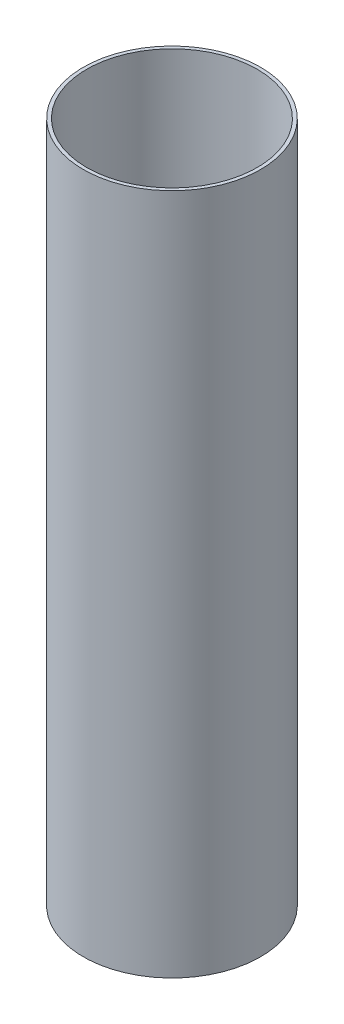
SolidWorks part; units mm, degrees
ref_plane "Front Plane" through (0, 0, 0) normal (0, 0, 1) x (1, 0, 0)
ref_plane "Top Plane" through (0, 0, 0) normal (0, 1, 0) x (1, 0, 0)
ref_plane "Right Plane" through (0, 0, 0) normal (1, 0, 0) x (0, 0, -1)
sketch "Sketch1" plane through (0, 0, 0) normal (0, 1, 0) x (1, 0, 0)
  circle A0 centre (0, 0) radius 39.624
  circle A1 centre (0, 0) radius 38.1
  dimension "D1" = 79.248
  dimension "D2" = 76.2
extrude "Boss-Extrude1" add sketch "Sketch1" along normal blind 304.8
